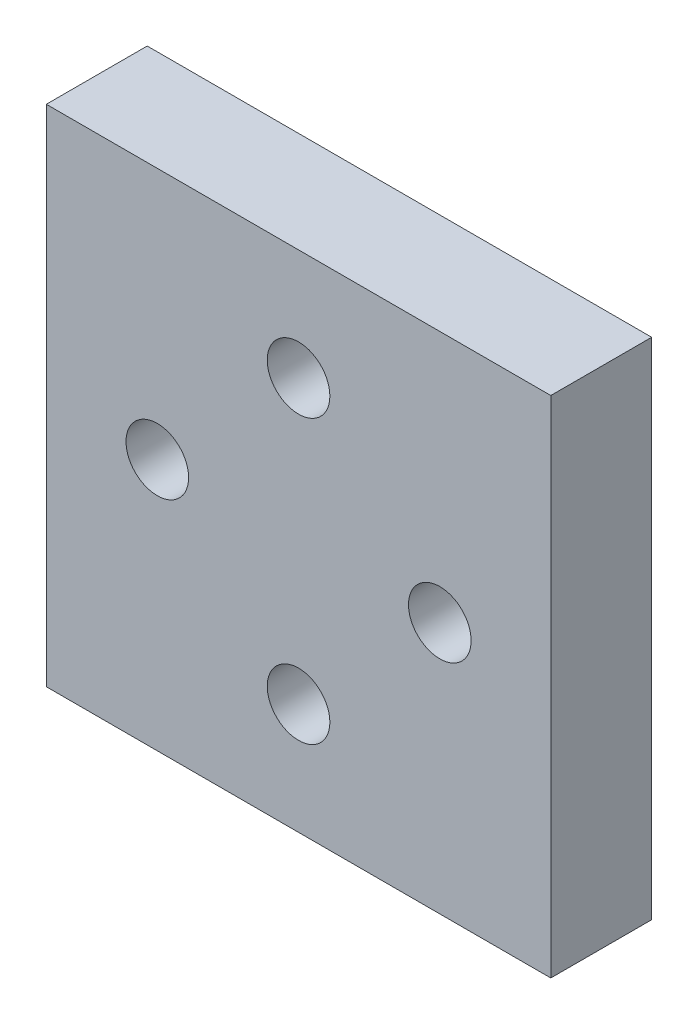
SolidWorks part; units mm, degrees
ref_plane "Front Plane" through (0, 0, 0) normal (0, 0, 1) x (1, 0, 0)
ref_plane "Top Plane" through (0, 0, 0) normal (0, 1, 0) x (1, 0, 0)
ref_plane "Right Plane" through (0, 0, 0) normal (1, 0, 0) x (0, 0, -1)
sketch "Sketch1" plane through (0, 0, 0) normal (0, 0, 1) x (1, 0, 0)
  line L1 (-12.5, 12.5) -> (12.5, 12.5)
  line L2 (-12.5, 12.5) -> (-12.5, -12.5)
  line L3 (-12.5, -12.5) -> (12.5, -12.5)
  line L4 (12.5, 12.5) -> (12.5, -12.5)
  line L5 (-12.5, 12.5) -> (12.5, -12.5) construction
  line L6 (-12.5, -12.5) -> (12.5, 12.5) construction
  circle A1 centre (0, 0) radius 1.5
  circle A2 centre (0, 7) radius 1.5515
  circle A4 centre (7, 0) radius 1.5515
  circle A6 centre (0, -7) radius 1.5515
  circle A8 centre (-7, 0) radius 1.5515
  circle A10 centre (-4.9497, 4.9497) radius 1.5515 [skipped]
  circle A11 centre (-4.9497, -4.9497) radius 1.5515 [skipped]
  circle A12 centre (4.9497, -4.9497) radius 1.5515 [skipped]
  circle A13 centre (4.9497, 4.9497) radius 1.5515 [skipped]
  point P0 (0, 0)
  point P26 (0, 0)
  point P29 (0, 0)
  dimension "D3" = 7
  dimension "D5" = 3.1031
  dimension "D1" = 25
  dimension "D2" = 25
  dimension "D4" = 8
extrude "Boss-Extrude1" add sketch "Sketch1" along normal blind 5
ref_plane "Plane1" through (0, 0, 5) normal (0, 0, 1) x (1, 0, 0)
sketch "Sketch2" plane through (0, 0, 5) normal (0, 0, 1) x (1, 0, 0)
  circle A0 centre (0, 0) radius 1.55
  dimension "D1" = 3.1
extrude "Boss-Extrude2" add sketch "Sketch2" against normal blind 5
